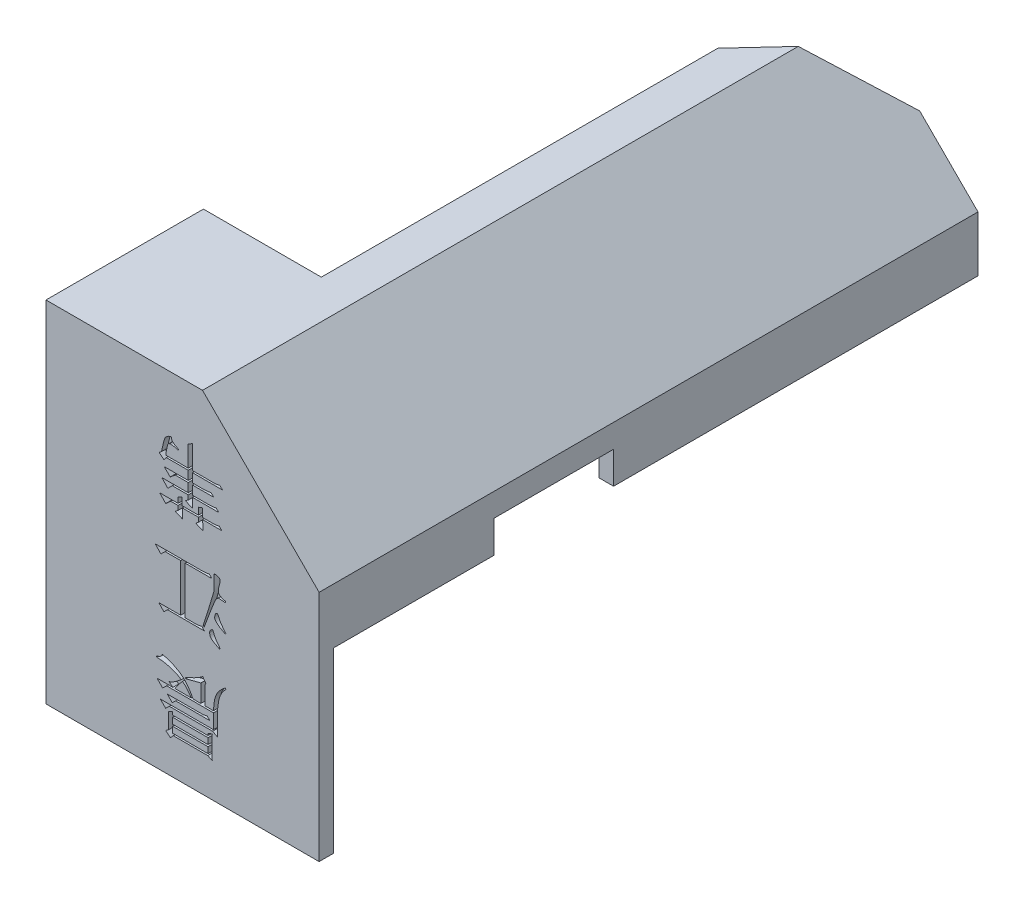
SolidWorks part; units mm, degrees
ref_plane "前视基准面" through (0, 0, 0) normal (0, 0, 1) x (1, 0, 0)
ref_plane "上视基准面" through (0, 0, 0) normal (0, 1, 0) x (1, 0, 0)
ref_plane "右视基准面" through (0, 0, 0) normal (1, 0, 0) x (0, 0, -1)
other "图形1"
sketch "草图2" plane through (0, 0, 0) normal (0, 1, 0) x (1, 0, 0)
  line L2 (23, -36) -> (23, -113)
  line L3 (23, -113) -> (-21, -113)
  line L4 (23, -36) -> (23.0433, 0)
  line L5 (23.0433, 0) -> (12.24, 0)
  line L7 (12.24, 0) -> (-12, -26.2527)
  line L9 (-12, -36) -> (-12, -26.2527)
  line L11 (-21, -86) -> (-12, -86)
  line L13 (-12, -86) -> (-12, -26.2527)
  line L14 (-21, -86) -> (-21, -113)
extrude "凸台-拉伸1" add sketch "草图2" along normal blind 10 contours L7 L5 L4 L2 L3 L14 L11 L13
sketch "草图3" plane through (0, 0, 0) normal (0, 0, -1) x (-1, 0, 0)
  line L0 (-12.24, 10) -> (-23.0433, 0)
  line L1 (-23.0433, 0) -> (-23.0433, 10)
  line L2 (-23.0433, 10) -> (-12.24, 10)
extrude "切除-拉伸1" cut sketch "草图3" against normal blind 200 contours L2 L0 L1
sketch "草图4" plane through (0, 0, 113) normal (0, 0, 1) x (1, 0, 0)
  line L0 (23, 0) -> (12.24, 10)
  line L1 (-4.38, 10) -> (12.24, 10)
  line L2 (-4.38, 10) -> (-4.38, 20)
  line L3 (12.24, 10) -> (-21, 10) construction
  line L4 (-4.38, 20) -> (1.48, 20)
  line L5 (1.48, 20) -> (12.24, 10)
extrude "凸台-拉伸2" add sketch "草图4" against normal blind 200 contours L5 L4 L2 L1
sketch "草图5" plane through (0, 0, 0) normal (0, -1, 0) x (1, 0, 0)
  line L0 (-4.38, 18) -> (12.24, 0)
  line L1 (12.24, 0) -> (12.24, -87)
  line L2 (12.24, -87) -> (-4.38, -87)
  line L3 (-4.38, -87) -> (-4.38, 18)
extrude "切除-拉伸2" cut sketch "草图5" against normal blind 200 contours L3 L0 L1 L2
sketch "草图6" plane through (0, 10, 0) normal (0, 1, 0) x (1, 0, 0)
  line L1 (-21, -86) -> (-4.38, -86)
  line L2 (-21, -86) -> (-21, -113)
  line L3 (-21, -113) -> (-4.38, -113)
  line L4 (-4.38, -86) -> (-4.38, -113)
extrude "凸台-拉伸3" add sketch "草图6" along normal blind 10 contours L2 L1 L4 L3
sketch "草图7" plane through (0, 0, 0) normal (0, -1, 0) x (-1, 0, 0)
  line L0 (21, -113) -> (24.6, -113)
  line L1 (24.6, -113) -> (24.6, -86)
  line L2 (24.6, -86) -> (21, -86)
  line L3 (21, -86) -> (21, -113)
extrude "凸台-拉伸4" add sketch "草图7" against normal blind 20 contours L3 L0 L1 L2
sketch "草图8" plane through (0, 0, 0) normal (0, 0, -1) x (-1, 0, 0)
  line L1 (-12.24, 0) -> (-12.24, 10)
  line L2 (-12.24, 0) -> (-22.24, 0)
  line L3 (-23.0433, 0) -> (-12.24, 0) construction
  line L4 (-22.24, 0) -> (-23.0433, 0)
  line L5 (-23.0433, 0) -> (-12.24, 10)
  line L6 (-22.24, 0) -> (-12.24, 10)
  line M5 (-12.24, 10) -> (-23.0433, 0)
  line M6 (-23.0433, 0) -> (-12.24, 0)
extrude "切除-拉伸3" cut sketch "草图8" against normal blind 200 contours L6 M6 M5
sketch "草图9" plane through (0, 0, 0) normal (0, 0, -1) x (-1, 0, 0)
  line L0 (-12.24, 10) -> (6.8383, 29.0783)
  line L1 (-12.24, 10) -> (-1.48, 20)
  line L2 (-1.48, 20) -> (4.38, 20)
  line L3 (4.38, 20) -> (-11.7741, 20)
extrude "凸台-拉伸5" add sketch "草图9" against normal blind 200 contours L1 L3 L0
sketch "草图10" plane through (0, 0, 0) normal (0, -1, 0) x (1, 0, 0)
  line L1 (1.48, 113) -> (12.24, 113)
  line L2 (1.48, 113) -> (1.48, 200)
  line L3 (1.48, 200) -> (12.24, 200)
  line L4 (12.24, 113) -> (12.24, 200)
extrude "切除-拉伸4" cut sketch "草图10" against normal blind 200
sketch "草图12" plane through (0, 0, 0) normal (0, -1, 0) x (1, 0, 0)
  line L0 (12.24, 0) -> (1.48, 0)
  line L1 (1.48, 0) -> (1.48, 11.6534)
  line L2 (1.48, 11.6534) -> (12.24, 0)
extrude "切除-拉伸5" cut sketch "草图12" against normal blind 200
sketch "草图13" plane through (0, 0, 0) normal (0, -1, 0) x (1, 0, 0)
  line L0 (22.24, 113) -> (22.24, 0) construction
  line L1 (-24.6, 113) -> (22.24, 113)
  line L2 (-24.6, 113) -> (-24.6, 110.5)
  line L3 (-24.6, 110.5) -> (22.24, 110.5)
  line L4 (22.24, 113) -> (22.24, 110.5)
extrude "凸台-拉伸6" add sketch "草图13" along normal blind 40 contours L2 L1 L4 L3
sketch "草图14" plane through (0, 0, 0) normal (0, -1, 0) x (1, 0, 0)
  line L0 (22.24, 110.5) -> (22.24, 0) construction
  line L1 (-24.6, 110.5) -> (22.24, 110.5)
  line L2 (-24.6, 110.5) -> (-24.6, 100.5)
  line L3 (-24.6, 100.5) -> (22.24, 100.5)
  line L4 (22.24, 110.5) -> (22.24, 100.5)
extrude "凸台-拉伸7" add sketch "草图14" along normal blind 9.5 contours L2 L1 L4 L3
sketch "草图15" plane through (0, 0, 0) normal (0, -1, 0) x (1, 0, 0)
  line L1 (22.24, 100.5) -> (22.24, 0) construction
  line L4 (22.24, 53) -> (22.24, 43)
  line L5 (22.24, 43) -> (7.24, 43)
  line L6 (7.24, 43) -> (7.24, 53)
  line L7 (7.24, 53) -> (22.24, 53)
extrude "凸台-拉伸8" add sketch "草图15" along normal blind 9.5 contours L4 L5 L6 L7
sketch "草图16" plane through (0, 0, 0) normal (0, -1, 0) x (1, 0, 0)
  line L0 (7.24, 53) -> (22.24, 53) construction
  line L1 (22.24, 100.5) -> (19.74, 100.5)
  line L2 (22.24, 100.5) -> (22.24, 53)
  line L3 (22.24, 53) -> (19.74, 53)
  line L4 (19.74, 100.5) -> (19.74, 53)
  line L10 (22.24, 0) -> (12.24, 0) construction
  line L11 (22.24, 43) -> (19.74, 43)
  line L12 (22.24, 43) -> (22.24, 0)
  line L13 (22.24, 0) -> (19.74, 0)
  line L14 (19.74, 43) -> (19.74, 0)
extrude "凸台-拉伸9" add sketch "草图16" along normal blind 9.5
sketch "草图17" plane through (0, -9.5, 0) normal (0, -1, 0) x (1, 0, 0)
  line L1 (19.74, 0) -> (21.24, 0)
  line L2 (19.74, 0) -> (19.74, 5)
  line L3 (19.74, 5) -> (21.24, 5)
  line L4 (21.24, 0) -> (21.24, 5)
extrude "切除-拉伸6" cut sketch "草图17" against normal blind 9.5 contours L2 L1 L4 L3
sketch "草图18" plane through (0, -9.5, 0) normal (0, -1, 0) x (-1, 0, 0)
  line L0 (-22.24, -83) -> (-22.24, -62.5)
  line L1 (-22.24, -110.5) -> (-22.24, 0) construction
  line L2 (-22.24, -83) -> (-19.74, -83)
  line L3 (-19.74, -100.5) -> (-19.74, -53) construction
  line L4 (-22.24, -62.5) -> (-19.74, -62.5)
  line L5 (-19.74, -62.5) -> (-19.74, -83)
  line M9 (-22.24, 0) -> (-22.24, -110.5)
  line M13 (-19.74, -100.5) -> (-19.74, -53)
extrude "切除-拉伸7" cut sketch "草图18" against normal blind 5.5 contours L4 L2 M9 M13
sketch "草图20" plane through (0, 0, 113) normal (0, 0, 1) x (1, 0, 0)
  text T0 "<r180>苇\r\n<r180>江\r\n<r180>晨\r\n</r>" font "Century Gothic" height in points 36
extrude "切除-拉伸8" cut sketch "草图20" against normal blind 1
